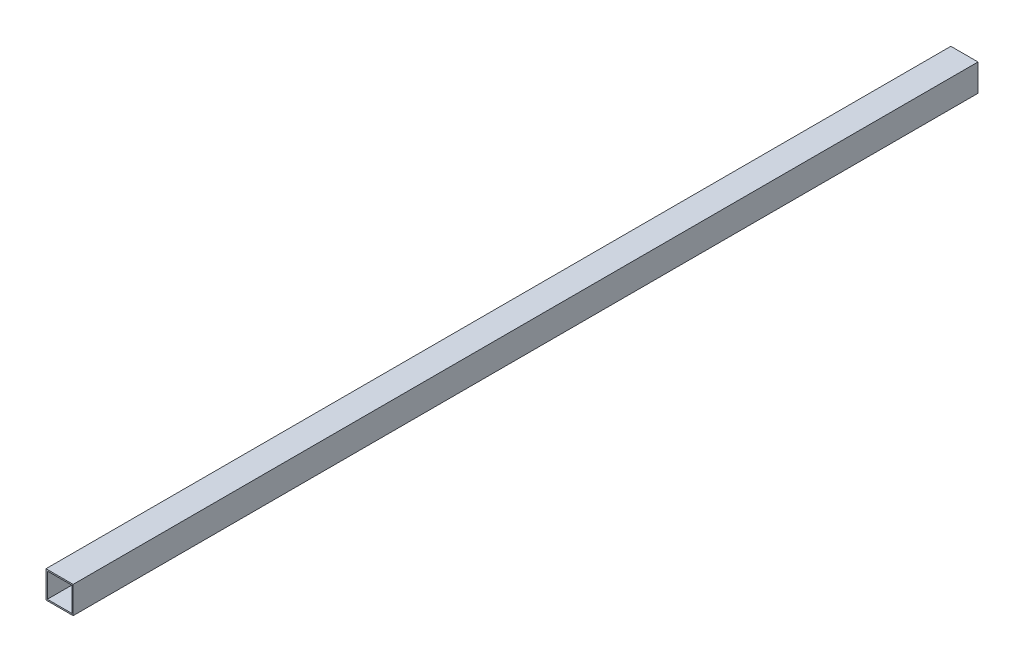
SolidWorks part; units mm, degrees
ref_plane "Front Plane" through (0, 0, 0) normal (0, 0, 1) x (1, 0, 0)
ref_plane "Top Plane" through (0, 0, 0) normal (0, 1, 0) x (1, 0, 0)
ref_plane "Right Plane" through (0, 0, 0) normal (1, 0, 0) x (0, 0, -1)
sketch "Sketch1" plane through (0, 0, 0) normal (0, 0, 1) x (1, 0, 0)
  line L0 (-13.5, 13.5) -> (-13.5, -13.5)
  line L1 (-15, 15) -> (15, 15)
  line L2 (-15, 15) -> (-15, -15)
  line L3 (-15, -15) -> (15, -15)
  line L4 (15, 15) -> (15, -15)
  line L5 (-15, 15) -> (15, -15) construction
  line L6 (-15, -15) -> (15, 15) construction
  line L7 (-13.5, -13.5) -> (13.5, -13.5)
  line L8 (13.5, 13.5) -> (13.5, -13.5)
  line L9 (-13.5, 13.5) -> (13.5, 13.5)
  point P0 (0, 0)
  dimension "D1" = 30
  dimension "D2" = 30
  dimension "D3" = 1.5
extrude "Boss-Extrude1" add sketch "Sketch1" along normal blind 1000
